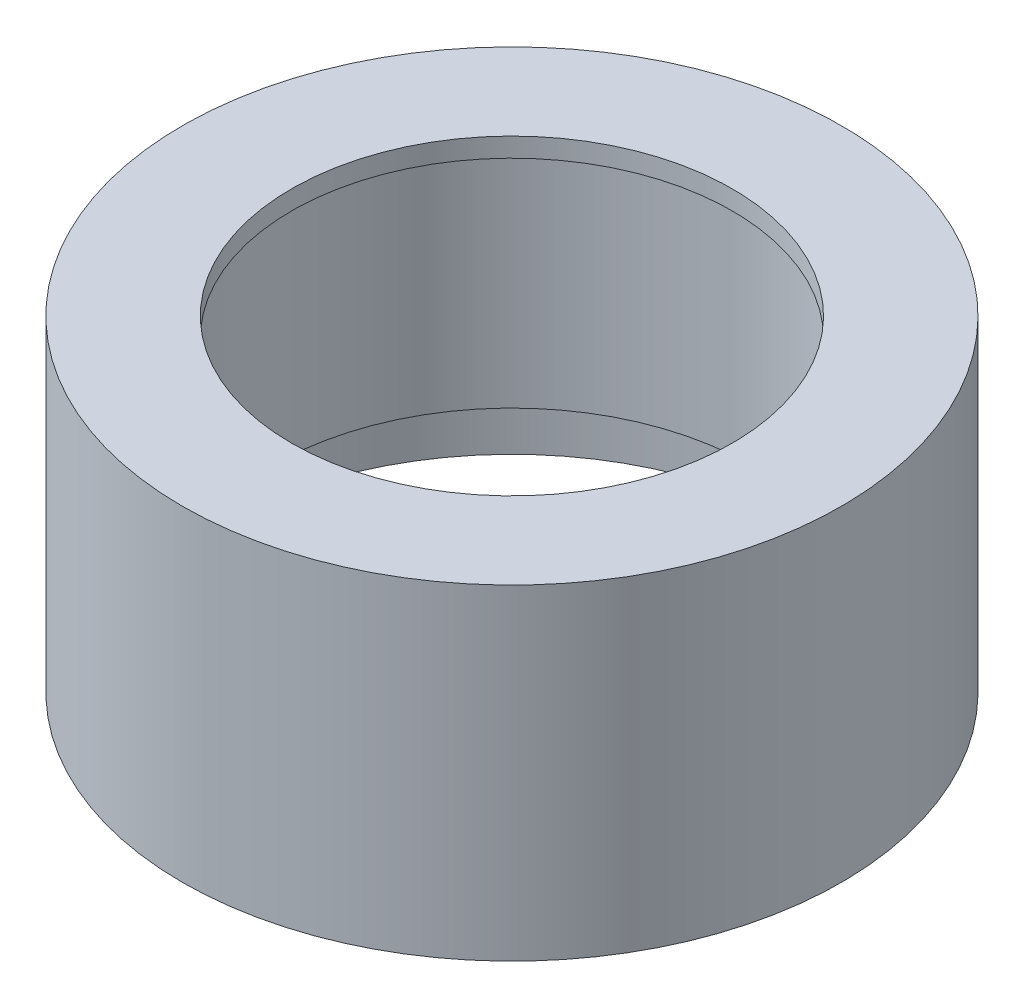
SolidWorks part; units mm, degrees
ref_plane "前视" through (0, 0, 0) normal (0, 0, 1) x (1, 0, 0)
ref_plane "上视" through (0, 0, 0) normal (0, 1, 0) x (1, 0, 0)
ref_plane "右视" through (0, 0, 0) normal (1, 0, 0) x (0, 0, -1)
sketch "Sketch1" plane through (0, 0, 0) normal (0, 1, 0) x (1, 0, 0)
  circle A0 centre (0, 0) radius 7.6
  circle A1 centre (0, 0) radius 8.6
  dimension "D1" = 15.2
  dimension "D2" = 1
extrude "Boss-Extrude1" add sketch "Sketch1" along normal blind 2
sketch "Sketch2" plane through (0, 2, 0) normal (0, 1, 0) x (1, 0, 0)
  circle A0 centre (0, 0) radius 8.6
  circle A1 centre (0, 0) radius 6.25
  circle A3 centre (0, 0) radius 8.6 construction
  dimension "D1" = 12.5
extrude "Boss-Extrude2" add sketch "Sketch2" along normal blind 6
sketch "Sketch3" plane through (0, 8, 0) normal (0, 1, 0) x (1, 0, 0)
  circle A0 centre (0, 0) radius 8.6
  circle A1 centre (0, 0) radius 8.6 construction
  circle A2 centre (0, 0) radius 5.75
  circle A3 centre (0, 0) radius 6.25 construction
  dimension "D1" = 0.5
extrude "Boss-Extrude3" add sketch "Sketch3" along normal blind 0.5
